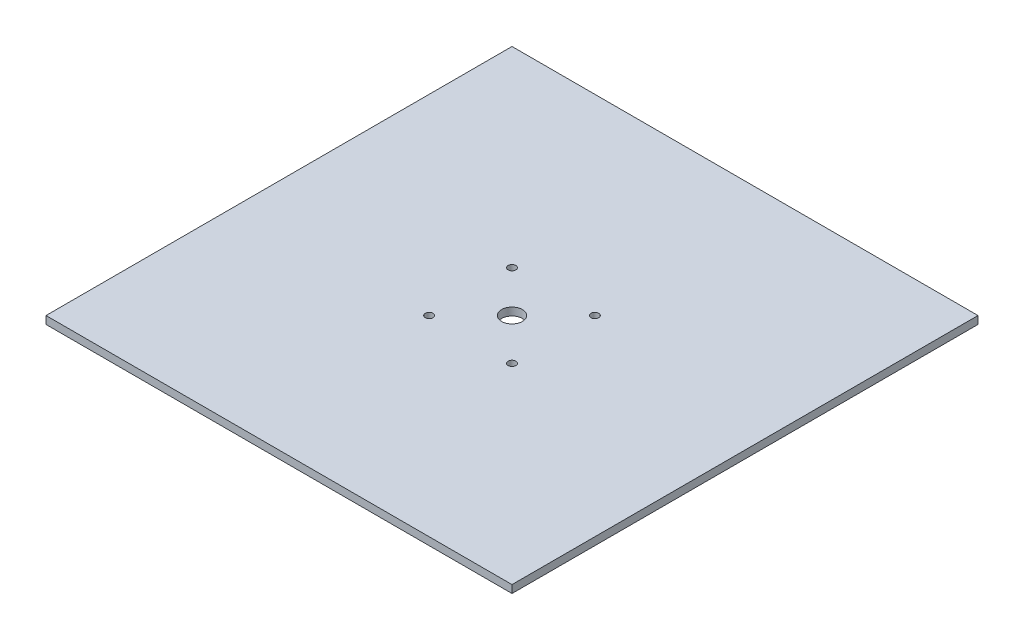
SolidWorks part; units mm, degrees
ref_plane "Front Plane" through (0, 0, 0) normal (0, 0, 1) x (1, 0, 0)
ref_plane "Top Plane" through (0, 0, 0) normal (0, 1, 0) x (1, 0, 0)
ref_plane "Right Plane" through (0, 0, 0) normal (1, 0, 0) x (0, 0, -1)
sketch "Sketch1" plane through (0, 0, 0) normal (0, 1, 0) x (1, 0, 0)
  line L1 (-90, -90) -> (90, -90)
  line L2 (-90, -90) -> (-90, 90)
  line L3 (-90, 90) -> (90, 90)
  line L4 (90, -90) -> (90, 90)
  line L5 (-90, -90) -> (90, 90) construction
  line L6 (-90, 90) -> (90, -90) construction
  point P0 (0, 0)
  dimension "D1" = 180
  dimension "D2" = 180
extrude "Boss-Extrude1" add sketch "Sketch1" along normal blind 3
sketch "Sketch2" plane through (0, 3, 0) normal (0, 1, 0) x (1, 0, 0)
  line L0 (0, 0) -> (0, 16) construction
  line L1 (0, 16) -> (-16, 16) construction
  circle A0 centre (0, 0) radius 4
  circle A1 centre (-16, 16) radius 1.5
  circle A2 centre (16, 16) radius 1.5
  circle A3 centre (16, -16) radius 1.5
  circle A4 centre (-16, -16) radius 1.5
  point P15 (0, 0)
  dimension "D1" = 8
  dimension "D4" = 3
  dimension "D2" = 16
  dimension "D3" = 16
  dimension "D5" = 4
extrude "Cut-Extrude1" cut sketch "Sketch2" against normal through all both and the other way through all
